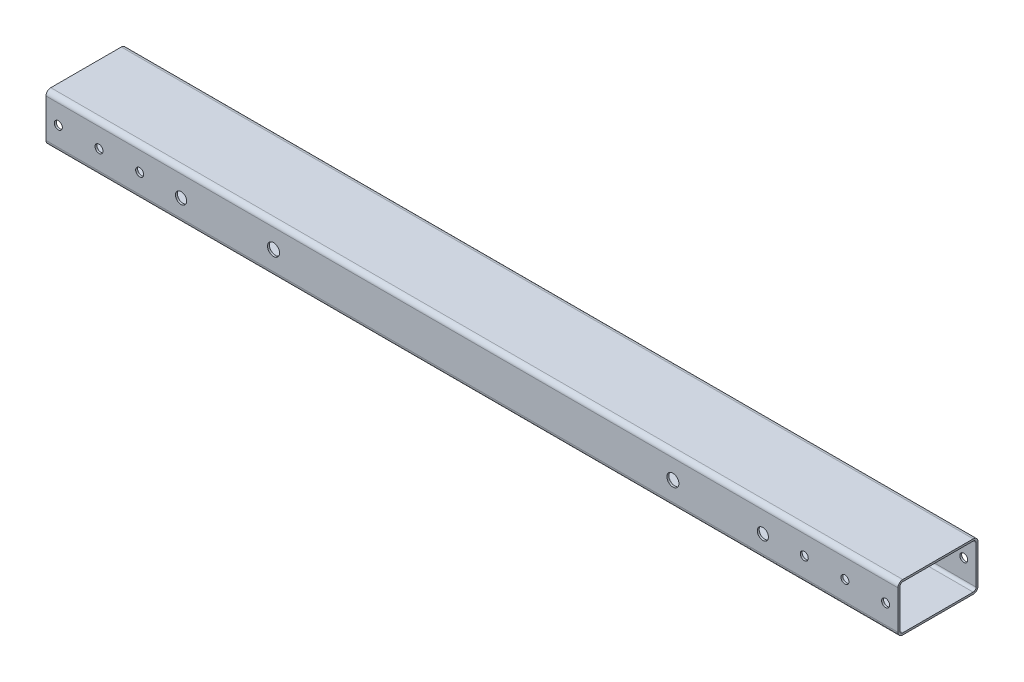
SolidWorks part; units mm, degrees
material "AISI 304"
ref_plane "Plano frontal" through (0, 0, 0) normal (0, 0, 1) x (1, 0, 0)
ref_plane "Plano superior" through (0, 0, 0) normal (0, 1, 0) x (1, 0, 0)
ref_plane "Plano direito" through (0, 0, 0) normal (1, 0, 0) x (0, 0, -1)
sketch "Esboço1" plane through (0, 0, 0) normal (0, 0, 1) x (1, 0, 0)
  line L0 (0, 0) -> (532, 0)
  dimension "D1" = 532
other "Tubo retangular 50 X 30 X 2.6(1)"
ref_plane "Plano1" through (0, 0, 0) normal (1, 0, 0) x (0, 1, 0)
sketch "Sketch1" plane through (0, 0, 0) normal (1, 0, 0) x (0, 1, 0)
  line L0 (-12, -23.8) -> (12, -23.8)
  line L1 (-13.8, -22) -> (-13.8, 22)
  line L2 (12, 23.8) -> (-12, 23.8)
  line L3 (13.8, 22) -> (13.8, -22)
  line L4 (-12, -25) -> (12, -25)
  line L5 (-15, -22) -> (-15, 22)
  line L6 (12, 25) -> (-12, 25)
  line L7 (15, 22) -> (15, -22)
  arc A0 (15, 22) -> (12, 25) centre (12, 22) ccw
  arc A1 (12, -25) -> (15, -22) centre (12, -22) ccw
  arc A2 (-15, -22) -> (-12, -25) centre (-12, -22) ccw
  arc A3 (-12, 25) -> (-15, 22) centre (-12, 22) ccw
  arc A4 (-12, 23.8) -> (-13.8, 22) centre (-12, 22) ccw
  arc A5 (13.8, 22) -> (12, 23.8) centre (12, 22) ccw
  arc A6 (12, -23.8) -> (13.8, -22) centre (12, -22) ccw
  arc A7 (-13.8, -22) -> (-12, -23.8) centre (-12, -22) ccw
  point P0 (0, 25)
  point P1 (15, 0)
  point P2 (0, -25)
  point P3 (-15, 0)
  point P4 (-15, 25)
  point P5 (15, 25)
  point P6 (15, -25)
  point P7 (-15, -25)
  point P8 (0, 0)
  point P33 (0, 0)
  dimension "D1" = 3
  dimension "Thickness" = 1.2
  dimension "V_leg" = 50
  dimension "H_leg" = 30
sketch "Esboço2" plane through (0, 0, -25) normal (0, 0, -1) x (-1, 0, 0)
  line L0 (0, -12) -> (0, 12) construction
  line L1 (-58.5, 0) -> (-33.1, 0) construction
  line L2 (-33.1, 0) -> (-7.7, 0) construction
  line L3 (-7.7, 0) -> (0, 0) construction
  line L4 (-266, 15) -> (-266, -15) construction
  line L5 (-532, 15) -> (0, 15) construction
  line L6 (-532, -15) -> (0, -15) construction
  line L7 (-524.3, 0) -> (-532, 0) construction
  line L8 (-498.9, 0) -> (-524.3, 0) construction
  line L9 (-473.5, 0) -> (-498.9, 0) construction
  circle A0 centre (-58.5, 0) radius 2.5
  circle A1 centre (-33.1, 0) radius 2.5
  circle A2 centre (-7.7, 0) radius 2.5
  circle A6 centre (-524.3, 0) radius 2.5
  circle A7 centre (-498.9, 0) radius 2.5
  circle A8 centre (-473.5, 0) radius 2.5
  dimension "D1" = 7.7
  dimension "D2" = 25.4
  dimension "D3" = 25.4
  dimension "D4" = 5
  dimension "D5" = 5
  dimension "D6" = 5
extrude "Corte-extrusão1" cut sketch "Esboço2" against normal through all
sketch "Esboço3" plane through (0, 0, -25) normal (0, 0, -1) x (-1, 0, 0)
  circle A0 centre (-185, -0.5) radius 3.25
  circle A1 centre (-111, -0.5) radius 3.25
  circle A2 centre (-373, -0.5) radius 3.25
extrude "Corte-extrusão2" [suppressed] cut sketch "Esboço3" against normal through all
sketch "Esboço4" plane through (0, 0, -25) normal (0, 0, -1) x (-1, 0, 0)
  circle A0 centre (-345, -0.5) radius 3.25
  circle A1 centre (-135, -0.5) radius 3.25
extrude "Corte-extrusão3" [suppressed] cut sketch "Esboço4" against normal through all
sketch "Esboço5" plane through (0, 0, -25) normal (0, 0, -1) x (-1, 0, 0)
  circle A0 centre (-391.4847, 0) radius 3.75
  circle A1 centre (-142.0847, 0) radius 3.75
  dimension "D1" = 7.5
  dimension "D2" = 7.5
extrude "Corte-extrusão4" cut sketch "Esboço5" against normal through all
sketch "Esboço6" plane through (0, 0, -25) normal (0, 0, -1) x (-1, 0, 0)
  circle A0 centre (-447.6522, -0.9847) radius 3.5
  circle A1 centre (-84.3478, -0.9847) radius 3.5
extrude "Corte-extrusão5" cut sketch "Esboço6" against normal through all
